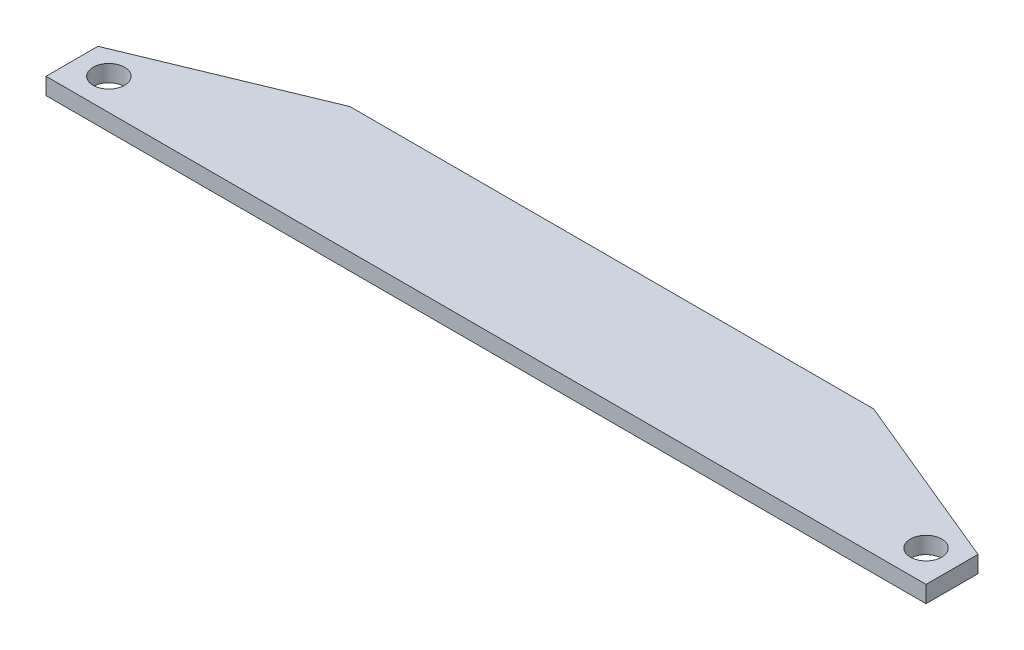
SolidWorks part; units mm, degrees
ref_plane "Front Plane" through (0, 0, 0) normal (0, 0, 1) x (1, 0, 0)
ref_plane "Top Plane" through (0, 0, 0) normal (0, 1, 0) x (1, 0, 0)
ref_plane "Right Plane" through (0, 0, 0) normal (1, 0, 0) x (0, 0, -1)
sketch "Sketch1" plane through (0, 0, 0) normal (0, 1, 0) x (1, 0, 0)
  line L0 (-42, 0) -> (42, 0)
  line L1 (42, 0) -> (42, 4.9584)
  line L2 (42, 4.9584) -> (25, 12)
  line L3 (25, 12) -> (-25, 12)
  line L4 (-25, 12) -> (-42, 4.9584)
  line L5 (-42, 4.9584) -> (-42, 0)
  point P4 (0, 0)
  dimension "D1" = 12
  dimension "D2" = 22.5
  dimension "D3" = 22.5
  dimension "D4" = 84
  dimension "D5" = 50
extrude "Boss-Extrude1" add sketch "Sketch1" along normal blind 1.6
sketch "Sketch4" plane through (0, 1.6, 0) normal (0, 1, 0) x (1, 0, 0)
  line L0 (-42, 0) -> (42, 0) construction
  line L1 (-42, 4.9584) -> (-42, 0) construction
  line L2 (0, -55) -> (0, 55) construction
  circle A0 centre (-39, 3) radius 1.5
  circle A1 centre (39, 3) radius 1.5
  dimension "D2" = 3
  dimension "D3" = 3
  dimension "D1" = 3
extrude "Cut-Extrude2" cut sketch "Sketch4" against normal up to surface (1.6 mm away) up to face at (0, 0, -5.6528)
